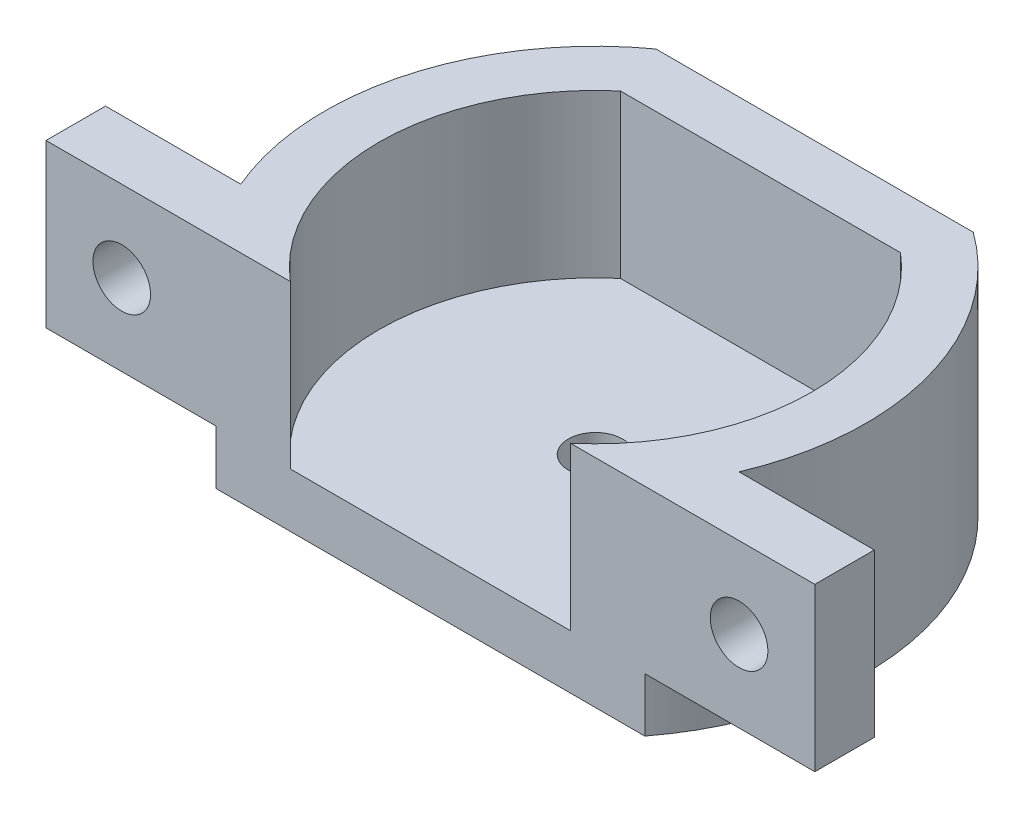
SolidWorks part; units mm, degrees
ref_plane "Front Plane" through (0, 0, 0) normal (0, 0, 1) x (1, 0, 0)
ref_plane "Top Plane" through (0, 0, 0) normal (0, 1, 0) x (1, 0, 0)
ref_plane "Right Plane" through (0, 0, 0) normal (1, 0, 0) x (0, 0, -1)
sketch "Sketch2" plane through (0, 0, 0) normal (0, 1, 0) x (1, 0, 0)
  line L0 (-7.4477, 10.287) -> (7.4477, 10.287)
  line L1 (-10.0635, -7.747) -> (-18.0443, -7.747)
  line L2 (-6.5734, -7.747) -> (-10.0635, -7.747)
  line L3 (6.5734, 7.747) -> (-6.5734, 7.747)
  line L4 (-10.0635, -7.747) -> (-6.5734, -7.747)
  line L5 (6.5734, -7.747) -> (10.0635, -7.747)
  line L6 (-18.0443, -7.747) -> (-18.0443, -4.953)
  line L7 (-18.0443, -4.953) -> (-11.6943, -4.953)
  line L8 (10.0635, -7.747) -> (18.0443, -7.747)
  line L9 (18.0443, -7.747) -> (18.0443, -4.953)
  line L10 (18.0443, -4.953) -> (11.6943, -4.953)
  arc A0 (-6.5734, 7.747) -> (-6.5734, -7.747) centre (0, 0) ccw
  arc A1 (6.5734, -7.747) -> (6.5734, 7.747) centre (0, 0) ccw
  arc A2 (11.6943, -4.953) -> (7.4477, 10.287) centre (0, 0) ccw
  arc A3 (-7.4477, 10.287) -> (-11.6943, -4.953) centre (0, 0) ccw
  dimension "D1" = 20.32
  dimension "D4" = 2.54
  dimension "D2" = 7.747
  dimension "D3" = 2.794
  dimension "D5" = 2.54
  dimension "D6" = 2.794
  dimension "D7" = 6.35
  dimension "D8" = 6.35
  dimension "D9" = 3.4901
  dimension "D10" = 3.4901
extrude "Boss-Extrude1" add sketch "Sketch2" along normal blind 7.62 contours L0 A3 L7 L6 L1 L2 A0 L3 A1 L5 L8 L9 L10 A2
sketch "Sketch3" plane through (0, 0, 0) normal (0, -1, 0) x (1, 0, 0)
  line L0 (7.4477, -10.287) -> (-7.4477, -10.287)
  line L1 (-10.0635, 7.747) -> (10.0635, 7.747)
  line L2 (6.5734, 7.747) -> (18.0443, 7.747) construction
  arc A0 (-10.0635, 7.747) -> (-7.4477, -10.287) centre (0, 0) ccw
  arc A1 (7.4477, -10.287) -> (10.0635, 7.747) centre (0, 0) ccw
  circle A2 centre (0, 0) radius 1.27
  dimension "D1" = 2.54
extrude "Boss-Extrude2" add sketch "Sketch3" along normal blind 2.54
hole_wizard "Tap Drill for #6-32 Tap1" positions "Sketch4" profile "Sketch5" hole size "#6-32" standard "ANSI Inch"
sketch "Sketch4" plane through (0, 0, 4.953) normal (0, 0, -1) x (-1, 0, 0)
  line L0 (-18.0443, 7.62) -> (-11.6943, 7.62) construction
  line L1 (18.0443, 7.62) -> (11.6943, 7.62) construction
  line L2 (18.0443, 7.62) -> (18.0443, 0) construction
  line L3 (-18.0443, 7.62) -> (-18.0443, 0) construction
  point P0 (-14.4883, 3.81)
  point P2 (14.4883, 3.81)
  dimension "D1" = 3.81
  dimension "D2" = 3.81
  dimension "D3" = 3.556
  dimension "D4" = 3.556
sketch "Sketch5" plane through (14.4883, 3.81, 4.953) normal (1, 0, 0) x (0, 1, 0)
  line L0 (0, 0) -> (0, 8.4327)
  line L1 (0, 8.4327) -> (1.3525, 7.62)
  line L2 (1.3525, 7.62) -> (1.3525, 0)
  line L5 (1.3525, 0) -> (0, 0)
  line L10 (0, 8.4327) -> (-1.3526, 7.62) construction
  line L11 (0, -6.35) -> (0, 107.95) construction
  dimension "Hole Dia." = 2.7051
  dimension "Hole Depth" = 7.62
  dimension "Drill Angle" = 118
